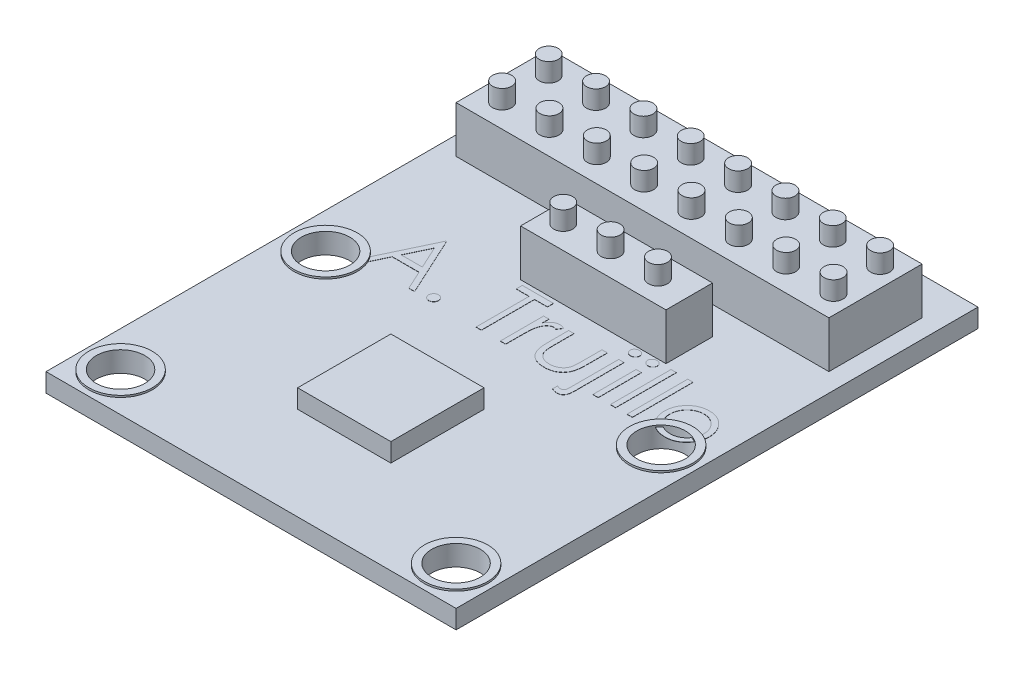
SolidWorks part; units mm, degrees
ref_plane "Front Plane" through (0, 0, 0) normal (0, 0, 1) x (1, 0, 0)
ref_plane "Top Plane" through (0, 0, 0) normal (0, 1, 0) x (1, 0, 0)
ref_plane "Right Plane" through (0, 0, 0) normal (1, 0, 0) x (0, 0, -1)
sketch "Sketch1" plane through (0, 0, 0) normal (0, 1, 0) x (1, 0, 0)
  line L1 (-11, 14) -> (11, 14)
  line L2 (-11, 14) -> (-11, -14)
  line L3 (-11, -14) -> (11, -14)
  line L4 (11, 14) -> (11, -14)
  line L5 (-11, 14) -> (11, -14) construction
  line L6 (-11, -14) -> (11, 14) construction
  point P0 (0, 0)
  dimension "D1" = 22
  dimension "D2" = 28
extrude "Boss-Extrude1" add sketch "Sketch1" along normal blind 1
sketch "Sketch2" plane through (0, 1, 0) normal (0, 1, 0) x (1, 0, 0)
  line L1 (-10, 12) -> (10, 12)
  line L2 (-10, 12) -> (-10, 7)
  line L3 (-10, 7) -> (10, 7)
  line L4 (10, 12) -> (10, 7)
  dimension "D1" = 10
  dimension "D2" = 7
  dimension "D3" = 5
  dimension "D4" = 20
extrude "Boss-Extrude2" add sketch "Sketch2" along normal blind 2.5
sketch "Sketch3" plane through (0, 3.5, 0) normal (0, 1, 0) x (1, 0, 0)
  line L0 (10, 9.5) -> (-10, 9.5) construction
  line L1 (10, 7) -> (10, 12) construction
  line L2 (-10, 12) -> (-10, 7) construction
  circle A0 centre (9, 8.25) radius 0.51
  circle A1 centre (6.46, 8.25) radius 0.51
  circle A2 centre (3.92, 8.25) radius 0.51
  circle A3 centre (1.38, 8.25) radius 0.51
  circle A4 centre (-1.16, 8.25) radius 0.51
  circle A5 centre (-3.7, 8.25) radius 0.51
  circle A6 centre (-6.24, 8.25) radius 0.51
  circle A7 centre (-8.78, 8.25) radius 0.51
  circle A8 centre (-8.78, 10.75) radius 0.51
  circle A9 centre (-6.24, 10.75) radius 0.51
  circle A10 centre (-3.7, 10.75) radius 0.51
  circle A11 centre (-1.16, 10.75) radius 0.51
  circle A12 centre (1.38, 10.75) radius 0.51
  circle A13 centre (3.92, 10.75) radius 0.51
  circle A14 centre (6.46, 10.75) radius 0.51
  circle A15 centre (9, 10.75) radius 0.51
  dimension "D1" = 1.02
  dimension "D2" = 9
  dimension "D3" = 8.25
  dimension "D4" = 8
extrude "Boss-Extrude3" add sketch "Sketch3" along normal blind 1
sketch "Sketch4" plane through (0, 1, 0) normal (0, 1, 0) x (1, 0, 0)
  line L1 (2.5, -9) -> (-2.5, -9)
  line L2 (2.5, -9) -> (2.5, -4)
  line L3 (2.5, -4) -> (-2.5, -4)
  line L4 (-2.5, -9) -> (-2.5, -4)
  point P4 (0, -4)
  dimension "D1" = 4
  dimension "D2" = 5
  dimension "D3" = 5
extrude "Boss-Extrude4" add sketch "Sketch4" along normal blind 1
sketch "Sketch5" plane through (0, 1, 0) normal (0, 1, 0) x (1, 0, 0)
  line L0 (0, 0) -> (0, -14) construction
  line L1 (-11, -14) -> (11, -14) construction
  line L2 (-11, -6.5) -> (11, -6.5) construction
  line L5 (-11, 14) -> (-11, -14) construction
  line L6 (11, -14) -> (11, 14) construction
  line L7 (-2.5, -4) -> (-2.5, -9) construction
  circle A0 centre (-9, -1) radius 1.3
  circle A1 centre (9, -1) radius 1.3
  circle A2 centre (9, -12) radius 1.3
  circle A3 centre (-9, -12) radius 1.3
  point P21 (-2.5, -6.5)
  dimension "D1" = 2.6
  dimension "D2" = 9
  dimension "D3" = 5.5
extrude "Cut-Extrude1" cut sketch "Sketch5" against normal blind 1
sketch "Sketch6" plane through (0, 1, 0) normal (0, 1, 0) x (1, 0, 0)
  circle A0 centre (-9, -12) radius 1.3 construction
  circle A1 centre (9, -12) radius 1.3 construction
  circle A2 centre (9, -1) radius 1.3 construction
  circle A3 centre (-9, -1) radius 1.3 construction
  circle A4 centre (-9, -12) radius 1.3
  circle A5 centre (9, -12) radius 1.3
  circle A6 centre (9, -1) radius 1.3
  circle A7 centre (-9, -1) radius 1.3
  circle A8 centre (-9, -1) radius 1.7
  circle A9 centre (9, -1) radius 1.7
  circle A10 centre (-9, -12) radius 1.7
  circle A11 centre (9, -12) radius 1.7
  dimension "D1" = 3.4
  dimension "D2" = 3.4
  dimension "D3" = 3.4
  dimension "D4" = 3.4
extrude "Boss-Extrude5" add sketch "Sketch6" along normal blind 0.1
sketch "Sketch7" plane through (0, 1, 0) normal (0, 1, 0) x (1, 0, 0)
  line L1 (-2.54, 5.5) -> (5.26, 5.5)
  line L2 (-2.54, 5.5) -> (-2.54, 3)
  line L3 (-2.54, 3) -> (5.26, 3)
  line L4 (5.26, 5.5) -> (5.26, 3)
  dimension "D1" = 2.5
  dimension "D2" = 7.8
  dimension "D3" = 3
  dimension "D4" = 2.54
extrude "Boss-Extrude6" add sketch "Sketch7" along normal blind 2.5
sketch "Sketch8" plane through (0, 3.5, 0) normal (0, 1, 0) x (1, 0, 0)
  line L0 (-2.54, 5.5) -> (-2.54, 3) construction
  circle A0 centre (-1.5, 4.25) radius 0.51
  circle A1 centre (1.04, 4.25) radius 0.51
  circle A2 centre (3.58, 4.25) radius 0.51
  point P5 (-2.54, 4.25)
  dimension "D3" = 1.02
  dimension "D1" = 1.5
  dimension "D2" = 3
extrude "Boss-Extrude7" add sketch "Sketch8" along normal blind 1
sketch "Sketch9" plane through (0, 1, 0) normal (0, 1, 0) x (1, 0, 0)
  text T0 "A. Trujillo"
  dimension "D1" = 8
  dimension "D2" = 3.6
extrude "Boss-Extrude8" add sketch "Sketch9" along normal blind 0.01
